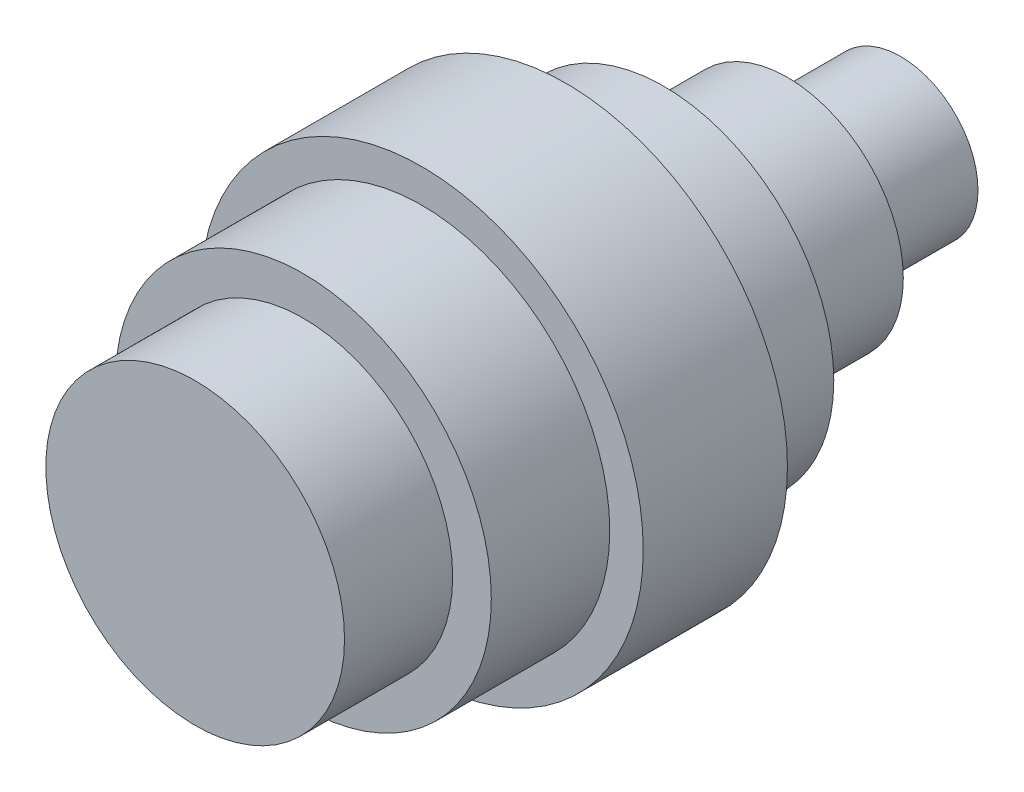
SolidWorks part; units mm, degrees
ref_plane "Front Plane" through (0, 0, 0) normal (0, 0, 1) x (1, 0, 0)
ref_plane "Top Plane" through (0, 0, 0) normal (0, 1, 0) x (1, 0, 0)
ref_plane "Right Plane" through (0, 0, 0) normal (1, 0, 0) x (0, 0, -1)
sketch "Sketch1" plane through (0, 0, 0) normal (1, 0, 0) x (0, 0, -1)
  line L1 (0, 0) -> (10.5, 0)
  line L2 (0, 0) -> (0, 14.5)
  line L3 (0, 14.5) -> (10.5, 14.5)
  line L4 (10.5, 0) -> (10.5, 14.5)
  line L5 (10.5, 0) -> (22, 0)
  line L6 (10.5, 0) -> (10.5, 18.25)
  line L7 (10.5, 18.25) -> (22, 18.25)
  line L8 (22, 0) -> (22, 18.25)
  line L9 (22, 0) -> (36, 0)
  line L10 (22, 0) -> (22, 21.5)
  line L11 (22, 21.5) -> (36, 21.5)
  line L12 (36, 0) -> (36, 21.5)
  line L13 (36, 0) -> (45.5, 0)
  line L14 (36, 0) -> (36, 16.5)
  line L15 (36, 16.5) -> (45.5, 16.5)
  line L16 (45.5, 0) -> (45.5, 16.5)
  line L17 (45.5, 0) -> (57.5, 0)
  line L18 (45.5, 0) -> (45.5, 11.25)
  line L19 (45.5, 11.25) -> (57.5, 11.25)
  line L20 (57.5, 0) -> (57.5, 11.25)
  line L21 (57.5, 0) -> (68.5, 0)
  line L22 (57.5, 0) -> (57.5, 7.5)
  line L23 (57.5, 7.5) -> (68.5, 7.5)
  line L24 (68.5, 0) -> (68.5, 7.5)
  dimension "D1" = 10.5
  dimension "D2" = 14.5
  dimension "D3" = 11.5
  dimension "D4" = 18.25
  dimension "D5" = 21.5
  dimension "D6" = 14
  dimension "D7" = 16.5
  dimension "D8" = 9.5
  dimension "D9" = 11.25
  dimension "D10" = 12
  dimension "D11" = 7.5
  dimension "D12" = 11
revolve "Revolve1" add sketch "Sketch1" angle 360 about L9
